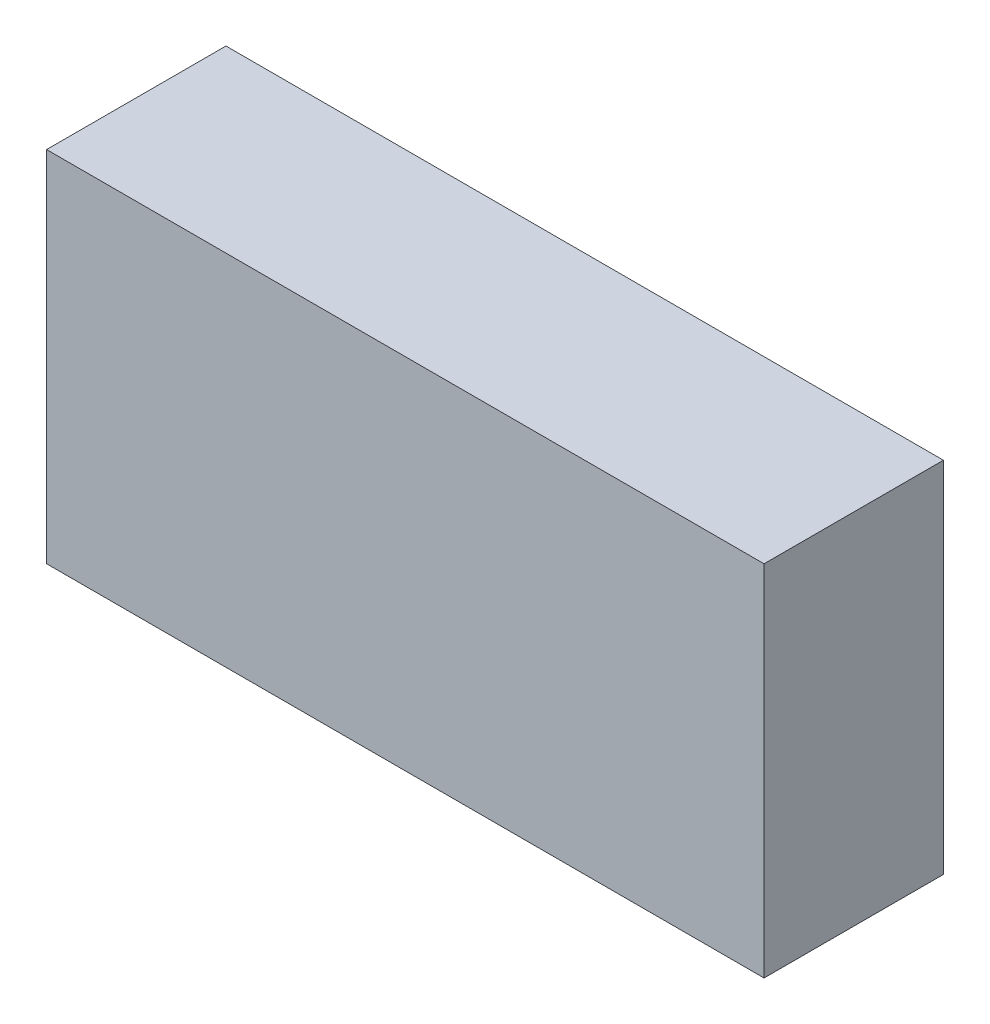
SolidWorks part; units mm, degrees
material "CA"
ref_plane "Front Plane" through (0, 0, 0) normal (0, 0, 1) x (1, 0, 0)
ref_plane "Top Plane" through (0, 0, 0) normal (0, 1, 0) x (1, 0, 0)
ref_plane "Right Plane" through (0, 0, 0) normal (1, 0, 0) x (0, 0, -1)
sketch "Sketch1" plane through (0, 0, 0) normal (0, 0, 1) x (1, 0, 0)
  line L1 (0, 0) -> (20, 0)
  line L2 (0, 0) -> (0, 10)
  line L3 (0, 10) -> (20, 10)
  line L4 (20, 0) -> (20, 10)
  dimension "D1" = 20
  dimension "D2" = 10
extrude "Boss-Extrude1" add sketch "Sketch1" along normal blind 5
